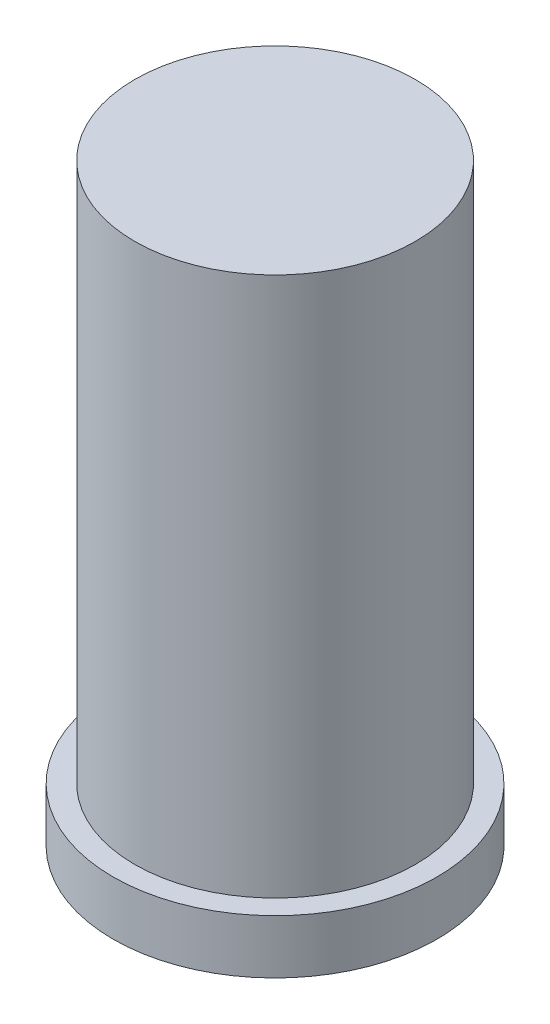
SolidWorks part; units mm, degrees
ref_plane "Front Plane" through (0, 0, 0) normal (0, 0, 1) x (1, 0, 0)
ref_plane "Top Plane" through (0, 0, 0) normal (0, 1, 0) x (1, 0, 0)
ref_plane "Right Plane" through (0, 0, 0) normal (1, 0, 0) x (0, 0, -1)
sketch "Sketch1" plane through (0, 0, 0) normal (0, 1, 0) x (1, 0, 0)
  circle A0 centre (0, 0) radius 1.5
  dimension "D1" = 3
extrude "Boss-Extrude1" add sketch "Sketch1" along normal blind 0.5
sketch "Sketch2" plane through (0, 0.5, 0) normal (0, 1, 0) x (1, 0, 0)
  circle A0 centre (0, 0) radius 1.3
  dimension "D1" = 2.6
extrude "Boss-Extrude2" add sketch "Sketch2" along normal blind 5
